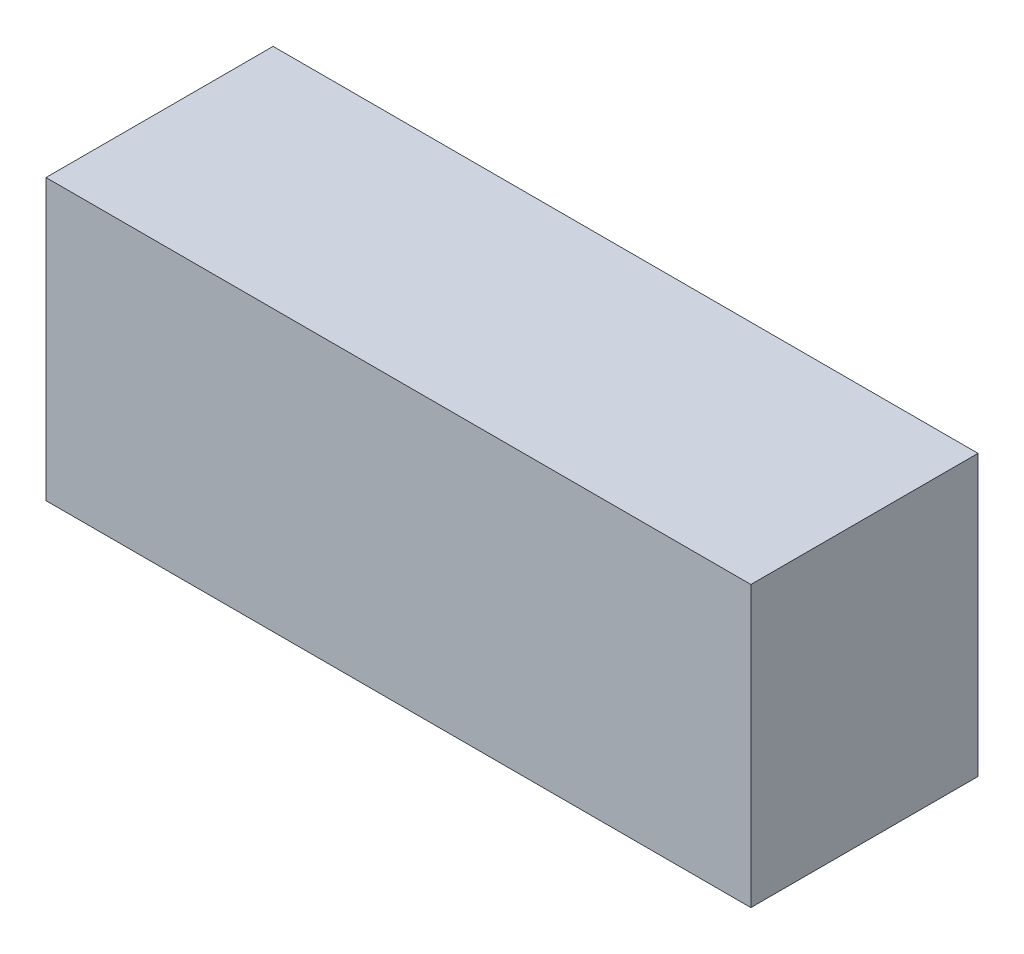
SolidWorks part; units mm, degrees
ref_plane "Front Plane" through (0, 0, 0) normal (0, 0, 1) x (1, 0, 0)
ref_plane "Top Plane" through (0, 0, 0) normal (0, 1, 0) x (1, 0, 0)
ref_plane "Right Plane" through (0, 0, 0) normal (1, 0, 0) x (0, 0, -1)
sketch "Sketch1" plane through (0, 0, 0) normal (0, 1, 0) x (1, 0, 0)
  line L1 (-67.5, -21.75) -> (67.5, -21.75)
  line L2 (-67.5, -21.75) -> (-67.5, 21.75)
  line L3 (-67.5, 21.75) -> (67.5, 21.75)
  line L4 (67.5, -21.75) -> (67.5, 21.75)
  line L5 (-67.5, -21.75) -> (67.5, 21.75) construction
  line L6 (-67.5, 21.75) -> (67.5, -21.75) construction
  point P0 (0, 0)
  dimension "D1" = 135
  dimension "D2" = 43.5
extrude "Boss-Extrude1" add sketch "Sketch1" along normal blind 53.6
